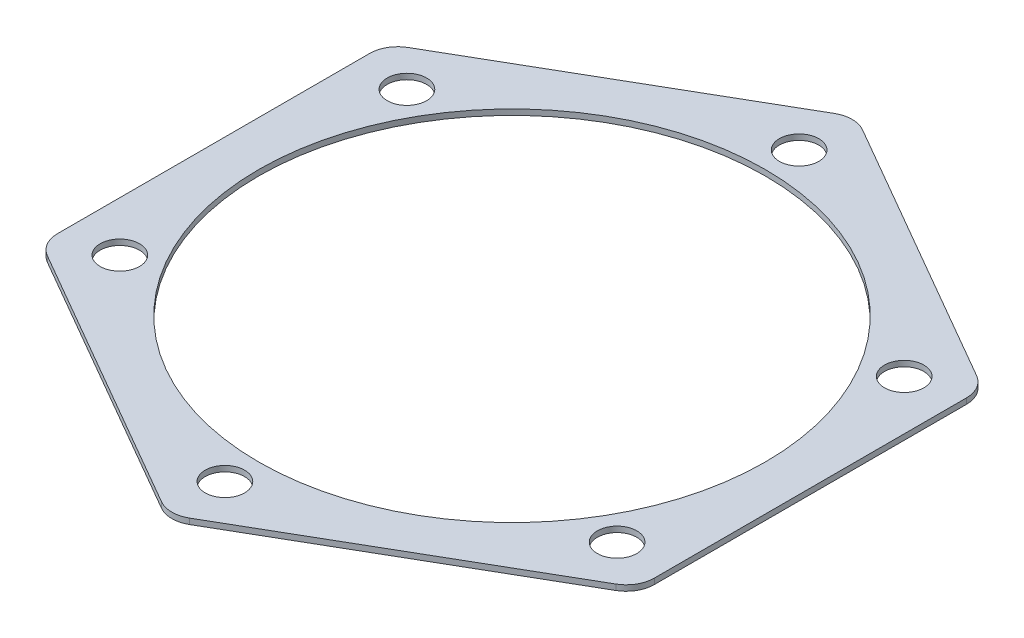
SolidWorks part; units mm, degrees
ref_plane "Front Plane" through (0, 0, 0) normal (0, 0, 1) x (1, 0, 0)
ref_plane "Top Plane" through (0, 0, 0) normal (0, 1, 0) x (1, 0, 0)
ref_plane "Right Plane" through (0, 0, 0) normal (1, 0, 0) x (0, 0, -1)
sketch "Sketch1" plane through (0, 0, 0) normal (0, 1, 0) x (1, 0, 0)
  line L1 (-50.5, -32.0429) -> (-2.5, -59.7558)
  line L2 (2.5, -59.7558) -> (50.5, -32.0429)
  line L3 (53, -27.7128) -> (53, 27.7128)
  line L4 (50.5, 32.0429) -> (2.5, 59.7558)
  line L5 (-2.5, 59.7558) -> (-50.5, 32.0429)
  line L6 (-53, 27.7128) -> (-53, -27.7128)
  circle A0 centre (0, 0) radius 53 construction
  circle A1 centre (0, 0) radius 45
  circle A2 centre (0, 0) radius 51 construction
  circle A3 centre (0, 51) radius 3.5
  circle A4 centre (44.1673, 25.5) radius 3.5
  circle A5 centre (44.1673, -25.5) radius 3.5
  circle A6 centre (0, -51) radius 3.5
  circle A7 centre (-44.1673, -25.5) radius 3.5
  circle A8 centre (-44.1673, 25.5) radius 3.5
  arc A9 (2.5, 59.7558) -> (-2.5, 59.7558) centre (0, 55.4256) ccw
  arc A10 (53, 27.7128) -> (50.5, 32.0429) centre (48, 27.7128) ccw
  arc A11 (50.5, -32.0429) -> (53, -27.7128) centre (48, -27.7128) ccw
  arc A12 (-2.5, -59.7558) -> (2.5, -59.7558) centre (0, -55.4256) ccw
  arc A13 (-50.5, -32.0429) -> (-53, -27.7128) centre (-48, -27.7128) cw
  arc A14 (-50.5, 32.0429) -> (-53, 27.7128) centre (-48, 27.7128) ccw
  point P25 (0, 0)
  point P26 (0, 61.1991)
  dimension "D2" = 102
  dimension "D3" = 90
  dimension "D4" = 7
  dimension "D6" = 5
  dimension "D1" = 106
  dimension "D5" = 6
extrude "Boss-Extrude1" add sketch "Sketch1" along normal blind 1
